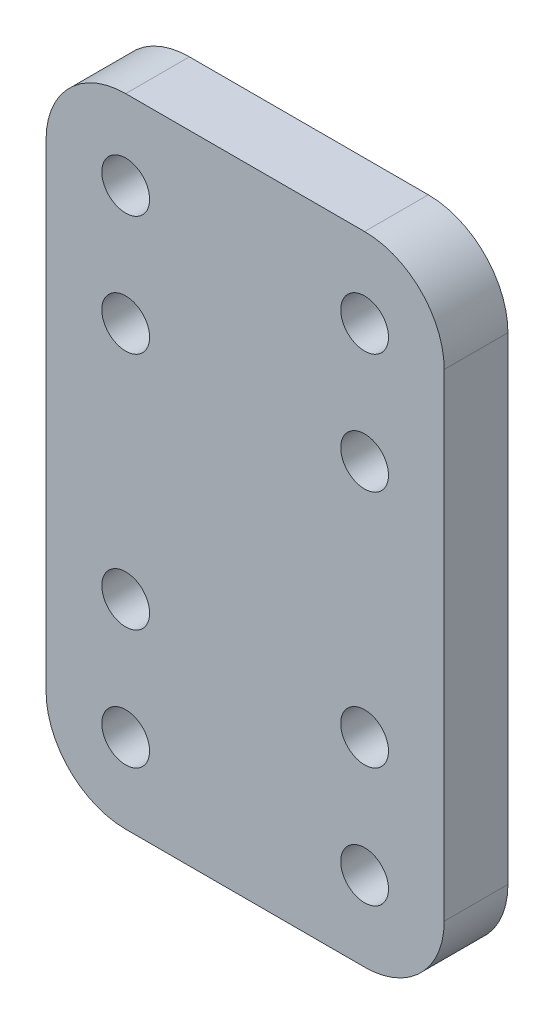
SolidWorks part; units mm, degrees
ref_plane "前视基准面" through (0, 0, 0) normal (0, 0, 1) x (1, 0, 0)
ref_plane "上视基准面" through (0, 0, 0) normal (0, 1, 0) x (1, 0, 0)
ref_plane "右视基准面" through (0, 0, 0) normal (1, 0, 0) x (0, 0, -1)
sketch "草图1" plane through (0, 0, 0) normal (0, 0, 1) x (1, 0, 0)
  line L1 (-12.5, 20) -> (12.5, 20)
  line L2 (-12.5, 20) -> (-12.5, -20)
  line L3 (-12.5, -20) -> (12.5, -20)
  line L4 (12.5, 20) -> (12.5, -20)
  line L5 (-12.5, 20) -> (12.5, -20) construction
  line L6 (-12.5, -20) -> (12.5, 20) construction
  circle A0 centre (-7.5, 15) radius 1.5
  circle A1 centre (7.5, 15) radius 1.5
  circle A2 centre (-7.5, -15) radius 1.5
  circle A3 centre (7.5, -15) radius 1.5
  circle A4 centre (-7.5, 7.5) radius 1.5
  circle A5 centre (7.5, 7.5) radius 1.5
  circle A6 centre (7.5, -7.5) radius 1.5
  circle A7 centre (-7.5, -7.5) radius 1.5
  point P0 (0, 0)
  dimension "D3" = 5
  dimension "D11" = 3
  dimension "D1" = 25
  dimension "D2" = 40
  dimension "D4" = 5
  dimension "D5" = 5
  dimension "D6" = 5
  dimension "D7" = 5
  dimension "D8" = 5
  dimension "D9" = 5
  dimension "D10" = 5
  dimension "D12" = 5
  dimension "D13" = 5
  dimension "D14" = 5
  dimension "D15" = 5
  dimension "D16" = 12.5
  dimension "D17" = 12.5
  dimension "D18" = 12.5
  dimension "D19" = 12.5
extrude "凸台-拉伸1" add sketch "草图1" along normal blind 4
fillet "圆角1" radius 5 4 edges at (12.5, -20, 2) (12.5, 20, 2) (-12.5, 20, 2) (-12.5, -20, 2)
